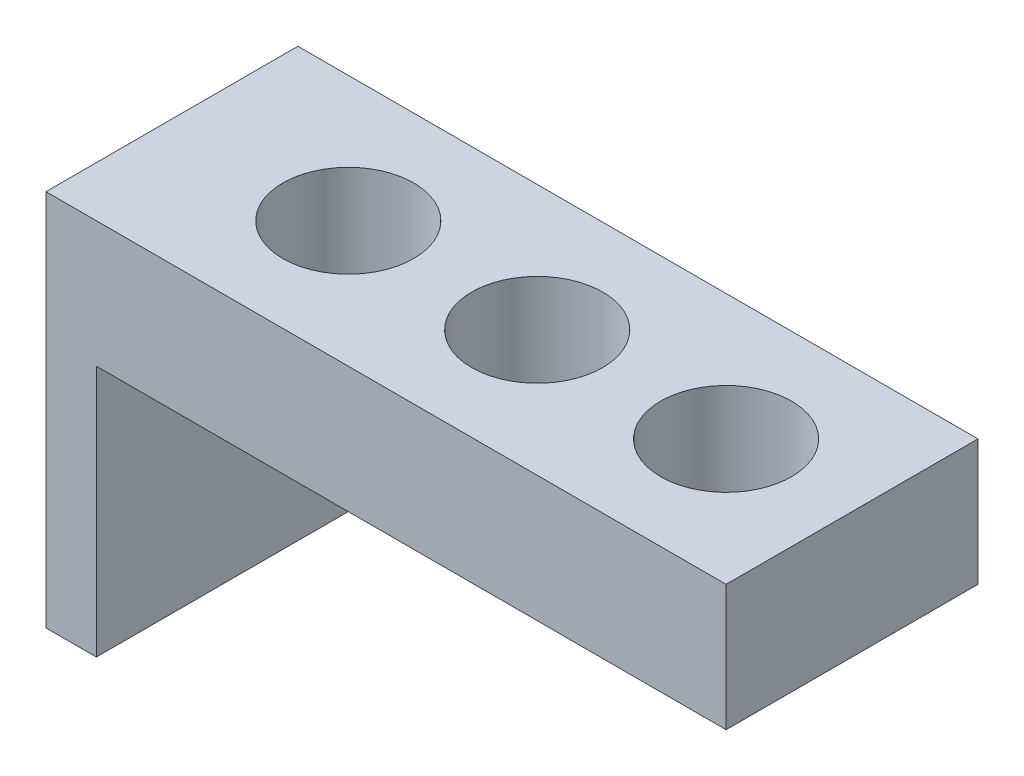
SolidWorks part; units mm, degrees
ref_plane "Front Plane" through (0, 0, 0) normal (0, 0, 1) x (1, 0, 0)
ref_plane "Top Plane" through (0, 0, 0) normal (0, 1, 0) x (1, 0, 0)
ref_plane "Right Plane" through (0, 0, 0) normal (1, 0, 0) x (0, 0, -1)
sketch "Sketch1" plane through (0, 0, 0) normal (0, 1, 0) x (1, 0, 0)
  line L0 (-139.2244, 0) -> (96.0116, 0) construction
  line L1 (0, 92.8454) -> (0, -61.6194) construction
  line L7 (-12.5, -5) -> (12.5, -5)
  line L8 (-12.5, -5) -> (-12.5, 5)
  line L9 (-12.5, 5) -> (12.5, 5)
  line L10 (12.5, -5) -> (12.5, 5)
  line L11 (-12.5, -5) -> (12.5, 5) construction
  line L12 (-12.5, 5) -> (12.5, -5) construction
  circle A12 centre (-7.5, 0) radius 2.6
  circle A13 centre (0, 0) radius 2.6
  circle A14 centre (7.5, 0) radius 2.6
  point P5 (0, 0)
  dimension "D3" = 5.2
  dimension "D4" = 5
  dimension "D5" = 3
  dimension "D6" = 5
  dimension "D1" = 25
  dimension "D2" = 10
extrude "Boss-Extrude1" add sketch "Sketch1" along normal blind 5
sketch "Sketch2" plane through (0, 0, 5) normal (0, 0, 1) x (1, 0, 0)
  line L0 (-12.5, 5) -> (-14.5, 5)
  line L1 (-14.5, 5) -> (-14.5, -10)
  line L2 (-14.5, -10) -> (-12.5, -10)
  line L3 (-12.5, -10) -> (-12.5, 5)
  line L4 (-12.5, 0) -> (12.5, 0) construction
  point P3 (0, 0)
  dimension "D1" = 2
  dimension "D2" = 10
extrude "Boss-Extrude2" add sketch "Sketch2" against normal blind 10
